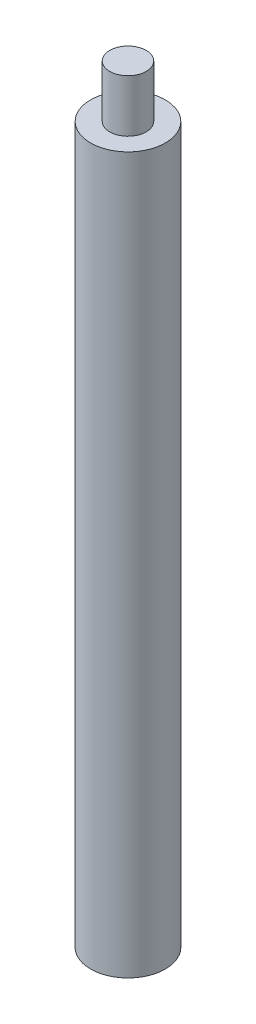
SolidWorks part; units mm, degrees
material "Polyetheretherketone (PEEK)"
ref_plane "Front Plane" through (0, 0, 0) normal (0, 0, 1) x (1, 0, 0)
ref_plane "Top Plane" through (0, 0, 0) normal (0, 1, 0) x (1, 0, 0)
ref_plane "Right Plane" through (0, 0, 0) normal (1, 0, 0) x (0, 0, -1)
sketch "Sketch2" plane through (0, 0, 0) normal (0, 1, 0) x (1, 0, 0)
  circle A0 centre (0, 0) radius 8.2
  dimension "D1" = 16.4
extrude "Boss-Extrude1" add sketch "Sketch2" along normal blind 157
sketch "Sketch3" plane through (0, 157, 0) normal (0, 1, 0) x (1, 0, 0)
  circle A0 centre (0, 0) radius 4
  circle A1 centre (0, 0) radius 8.2 construction
  dimension "D1" = 8
sketch "Sketch4" plane through (0, 0, 0) normal (0, -1, 0) x (1, 0, 0)
  circle A0 centre (0, 0) radius 2.1
  circle A1 centre (0, 0) radius 8.2 construction
  dimension "D1" = 4.2
extrude "Cut-Extrude2" cut sketch "Sketch4" against normal blind 10
extrude "Boss-Extrude2" add sketch "Sketch3" along normal blind 11.5
